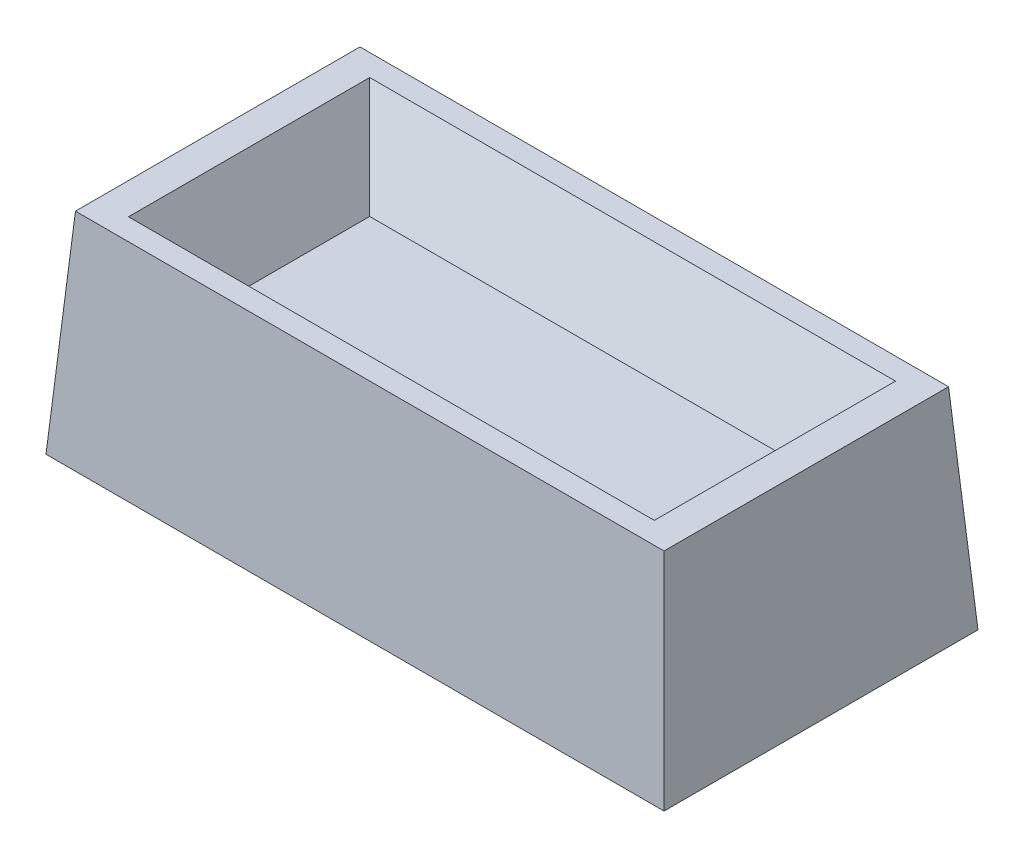
SolidWorks part; units mm, degrees
ref_plane "Front Plane" through (0, 0, 0) normal (0, 0, 1) x (1, 0, 0)
ref_plane "Top Plane" through (0, 0, 0) normal (0, 1, 0) x (1, 0, 0)
ref_plane "Right Plane" through (0, 0, 0) normal (1, 0, 0) x (0, 0, -1)
sketch "Sketch1" plane through (0, 0, 0) normal (0, 1, 0) x (1, 0, 0)
  line L1 (-102.8928, -52.2674) -> (102.8928, -52.2674)
  line L2 (-102.8928, -52.2674) -> (-102.8928, 52.2674)
  line L3 (-102.8928, 52.2674) -> (102.8928, 52.2674)
  line L4 (102.8928, -52.2674) -> (102.8928, 52.2674)
  line L5 (-102.8928, -52.2674) -> (102.8928, 52.2674) construction
  line L6 (-102.8928, 52.2674) -> (102.8928, -52.2674) construction
  point P0 (0, 0)
extrude "Boss-Extrude1" add sketch "Sketch1" along normal blind 70.104 draft 4
sketch "Sketch2" plane through (0, 70.104, 0) normal (0, 1, 0) x (1, 0, 0)
  line L1 (-72.8794, -25.487) -> (72.8794, -25.487)
  line L2 (-72.8794, -25.487) -> (-72.8794, 25.487)
  line L3 (-72.8794, 25.487) -> (72.8794, 25.487)
  line L4 (72.8794, -25.487) -> (72.8794, 25.487)
  line L5 (-72.8794, -25.487) -> (72.8794, 25.487) construction
  line L6 (-72.8794, 25.487) -> (72.8794, -25.487) construction
  point P0 (0, 0)
extrude "Cut-Extrude1" cut sketch "Sketch2" against normal blind 25.4
draft "Draft1" type of draft neutral plane draft angle 30 faces to draft 4 face at (0, 57.404, 25.487) face at (72.8794, 57.404, 0) face at (0, 57.404, -25.487) face at (-72.8794, 57.404, 0) neutral plane through (0, 44.704, 0) neutral plane normal (0, 1, 0) parameters "D1"=30
